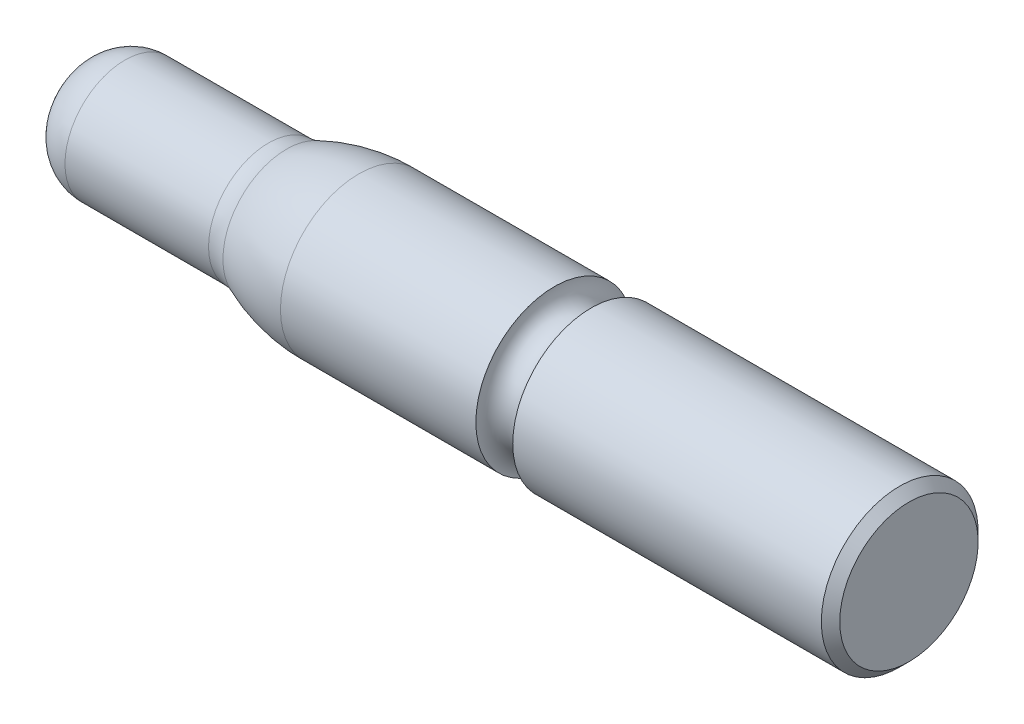
SolidWorks part; units mm, degrees
material "Cast Alloy Steel"
ref_plane "Front Plane" through (0, 0, 0) normal (0, 0, 1) x (1, 0, 0)
ref_plane "Top Plane" through (0, 0, 0) normal (0, 1, 0) x (1, 0, 0)
ref_plane "Right Plane" through (0, 0, 0) normal (1, 0, 0) x (0, 0, -1)
sketch "Sketch1" plane through (0, 0, 0) normal (0, 0, 1) x (1, 0, 0)
  line L0 (0, 0) -> (71.6562, 0)
  line L1 (79.6562, 0) -> (148.5685, 0)
  line L2 (148.5685, 17) -> (148.5685, 0)
  line L3 (148.5685, 17) -> (79.6562, 17)
  line L4 (71.6562, 17) -> (29.2936, 17)
  line L5 (11.858, 13) -> (-31.4315, 13)
  line L6 (-31.4315, 13) -> (-31.4315, 0)
  line L7 (-31.4315, 0) -> (0, 0)
  arc A0 (71.6562, 0) -> (79.6562, 0) centre (75.6562, 0) cw
  arc A1 (79.6562, 17) -> (71.6562, 17) centre (75.6562, 17) cw
  arc A2 (29.2936, 17) -> (11.858, 13) centre (29.2936, -23) ccw
  dimension "D2" = 4
  dimension "D3" = 4
  dimension "D4" = 40
  dimension "D7" = 23
  dimension "D1" = 17
  dimension "D5" = 13
revolve "Revolve1" add sketch "Sketch1" angle 360 about L0
fillet "Fillet1" radius 10 2 edges at (11.858, 0, 13) (-31.4315, 0, 13)
chamfer "Chamfer1" distance 2 angle 45 1 edges at (148.5685, 0, 17)
